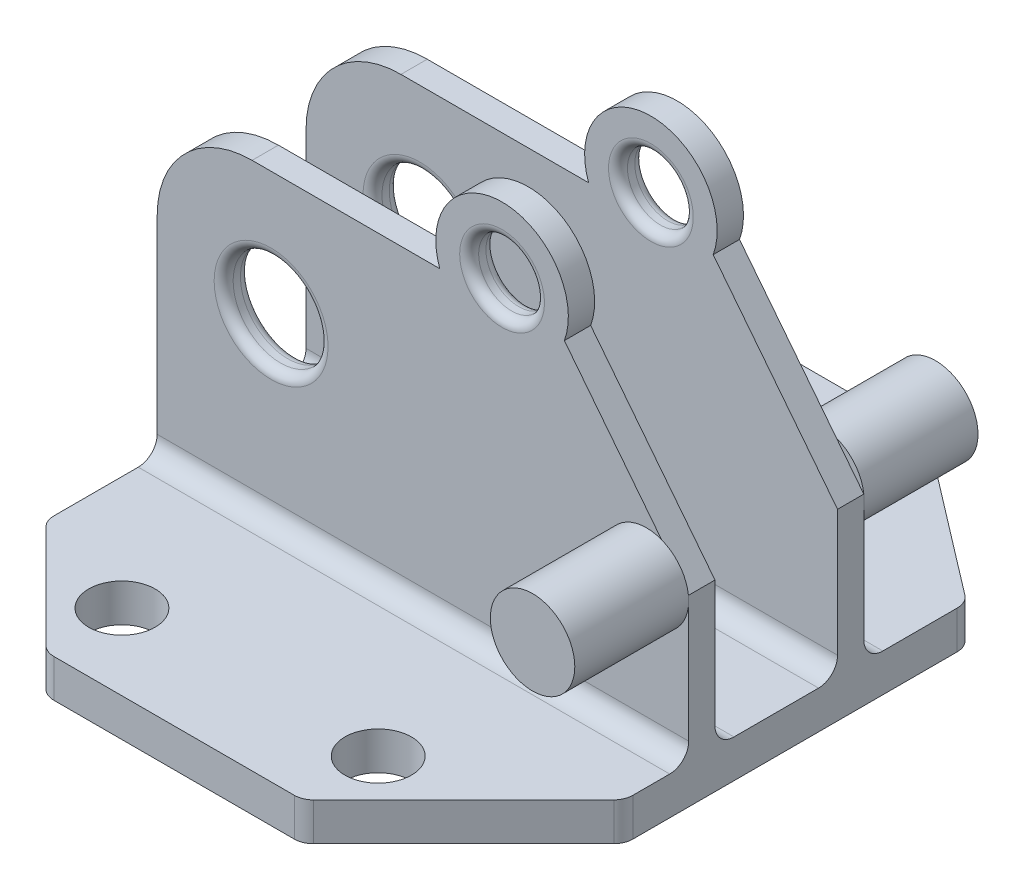
SolidWorks part; units mm, degrees
material "Cast Carbon Steel"
ref_plane "Front Plane" through (0, 0, 0) normal (0, 0, 1) x (1, 0, 0)
ref_plane "Top Plane" through (0, 0, 0) normal (0, 1, 0) x (1, 0, 0)
ref_plane "Right Plane" through (0, 0, 0) normal (1, 0, 0) x (0, 0, -1)
sketch "Sketch1" plane through (0, 0, 0) normal (0, 1, 0) x (1, 0, 0)
  line L0 (0, 0) -> (0, -42)
  line L1 (0, -42) -> (12, -54)
  line L2 (12, -54) -> (39, -54)
  line L3 (39, -54) -> (56, -37)
  line L4 (56, -37) -> (56, -1)
  line L5 (56, -1) -> (39, 12)
  line L6 (39, 12) -> (12, 12)
  line L7 (12, 12) -> (0, 0)
  dimension "D1" = 66
  dimension "D2" = 56
  dimension "D3" = 27
  dimension "D4" = 27
  dimension "D5" = 36
  dimension "D6" = 12
  dimension "D7" = 12
  dimension "D9" = 12
  dimension "D10" = 135
extrude "Boss-Extrude1" add sketch "Sketch1" along normal blind 4 contours L7 L0 L1 L2 L3 L4 L5 L6
sketch "Sketch2" plane through (0, 4, 0) normal (0, 1, 0) x (1, 0, 0)
  line L0 (12, -54) -> (39, -54) construction
  line L1 (39, 12) -> (12, 12) construction
  line L3 (0, 0) -> (0, -42) construction
  line L4 (56, -37) -> (56, -1) construction
  circle A0 centre (12, 4) radius 3.5
  circle A1 centre (39, 4) radius 3.5
  circle A2 centre (12, -46) radius 3.5
  circle A3 centre (39, -46) radius 3.5
  dimension "D7" = 7
  dimension "D8" = 7
  dimension "D9" = 7
  dimension "D10" = 7
  dimension "D1" = 8
  dimension "D2" = 8
  dimension "D3" = 8
  dimension "D4" = 8
  dimension "D5" = 12
  dimension "D6" = 12
  dimension "D11" = 17
  dimension "D12" = 17
extrude "Cut-Extrude1" cut sketch "Sketch2" against normal blind 4
fillet "Fillet1" radius 2 8 edges at (0, 2, 0) (12, 2, -12) (39, 2, -12) (56, 2, 1) (56, 2, 37) (39, 2, 54) (12, 2, 54) (0, 2, 42)
sketch "Sketch4" plane through (0, 4, 0) normal (0, 1, 0) x (1, 0, 0)
  line L0 (0, -21) -> (56, -21) construction
  line L1 (0, -0.8284) -> (0, -41.1716) construction
  line L2 (56, -36.1716) -> (56, -1.9883) construction
  line L4 (0, -11.8302) -> (56, -11.8302)
  line L5 (0, -11.8302) -> (0, -14.6002)
  line L6 (0, -14.6002) -> (56, -14.6002)
  line L7 (56, -11.8302) -> (56, -14.6002)
  line L8 (0, -27.5126) -> (56, -27.5126)
  line L9 (0, -27.5126) -> (0, -30.2826)
  line L10 (0, -30.2826) -> (56, -30.2826)
  line L11 (56, -27.5126) -> (56, -30.2826)
  dimension "D1" = 2.77
  dimension "D2" = 2.77
extrude "Boss-Extrude2" add sketch "Sketch4" along normal blind 32
sketch "Sketch5" plane through (0, 0, 30.2826) normal (0, 0, 1) x (1, 0, 0)
  line L0 (0, 36) -> (0, 4) construction
  line L1 (0, 4) -> (56, 4) construction
  circle A0 centre (12, 23) radius 5
  dimension "D3" = 10
  dimension "D1" = 12
  dimension "D2" = 19
extrude "Cut-Extrude2" cut sketch "Sketch5" against normal through all
sketch "Sketch6" plane through (0, 0, 30.2826) normal (0, 0, 1) x (1, 0, 0)
  line L0 (42.9002, 36) -> (56, 19.3166)
  line L1 (0, 36) -> (56, 36) construction
  line L2 (56, 36) -> (56, 4) construction
  line L3 (42.9002, 36) -> (56, 36)
  line L4 (56, 36) -> (56, 19.3166)
extrude "Cut-Extrude3" cut sketch "Sketch6" against normal through all
sketch "Sketch7" plane through (0, 0, 30.2826) normal (0, 0, 1) x (1, 0, 0)
  circle A0 centre (51.5499, 18.7942) radius 4.4501
extrude "Boss-Extrude3" add sketch "Sketch7" along normal blind 12
sketch "Sketch8" plane through (0, 0, 11.8302) normal (0, 0, -1) x (-1, 0, 0)
  circle A0 centre (-51.5499, 18.7942) radius 4.4806
extrude "Boss-Extrude4" add sketch "Sketch8" along normal blind 12
sketch "Sketch9" plane through (0, 0, 30.2826) normal (0, 0, 1) x (1, 0, 0)
  circle A0 centre (36.3363, 38.3864) radius 6.9843
extrude "Boss-Extrude5" add sketch "Sketch9" against normal up to surface (2.77 mm away) up to face at (17, 23, 27.5126)
sketch "Sketch10" plane through (0, 0, 11.8302) normal (0, 0, -1) x (-1, 0, 0)
  circle A0 centre (-36.3363, 38.3864) radius 6.9843
extrude "Boss-Extrude6" add sketch "Sketch10" against normal up to surface (2.77 mm away) up to face at (7, 23, 14.6002)
sketch "Sketch11" plane through (0, 0, 11.8302) normal (0, 0, -1) x (-1, 0, 0)
  circle A0 centre (-36.3363, 38.3864) radius 3.4674
extrude "Cut-Extrude4" cut sketch "Sketch11" against normal through all
fillet "Fillet2" radius 2 4 edges at (28, 4, 30.2826) (28, 4, 14.6002) (28, 4, 27.5126) (28, 4, 11.8302)
fillet "Fillet3" radius 10 2 edges at (0, 36, 13.2152) (0, 36, 28.8976)
fillet "Fillet4" radius 1 4 edges at (32.8689, 38.3864, 30.2826) (39.8037, 38.3864, 27.5126) (32.8689, 38.3864, 14.6002) (32.8689, 38.3864, 11.8302)
fillet "Fillet5" radius 1 4 edges at (17, 23, 30.2826) (17, 23, 27.5126) (7, 23, 14.6002) (17, 23, 11.8302)
